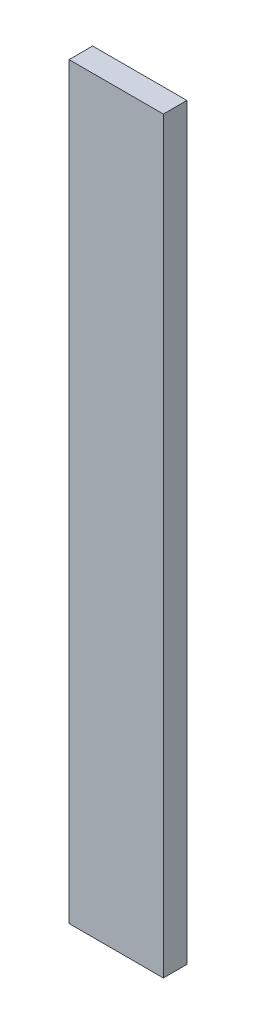
SolidWorks part; units mm, degrees
ref_plane "Front Plane" through (0, 0, 0) normal (0, 0, 1) x (1, 0, 0)
ref_plane "Top Plane" through (0, 0, 0) normal (0, 1, 0) x (1, 0, 0)
ref_plane "Right Plane" through (0, 0, 0) normal (1, 0, 0) x (0, 0, -1)
sketch "Sketch1" plane through (0, 0, 0) normal (0, 0, 1) x (1, 0, 0)
  line L1 (0, 0) -> (0.8001, 0)
  line L2 (0, 0) -> (0, 6.35)
  line L3 (0, 6.35) -> (0.8001, 6.35)
  line L4 (0.8001, 0) -> (0.8001, 6.35)
  dimension "D1" = 0.8001
  dimension "D2" = 6.35
extrude "Boss-Extrude1" add sketch "Sketch1" along normal blind 0.2
